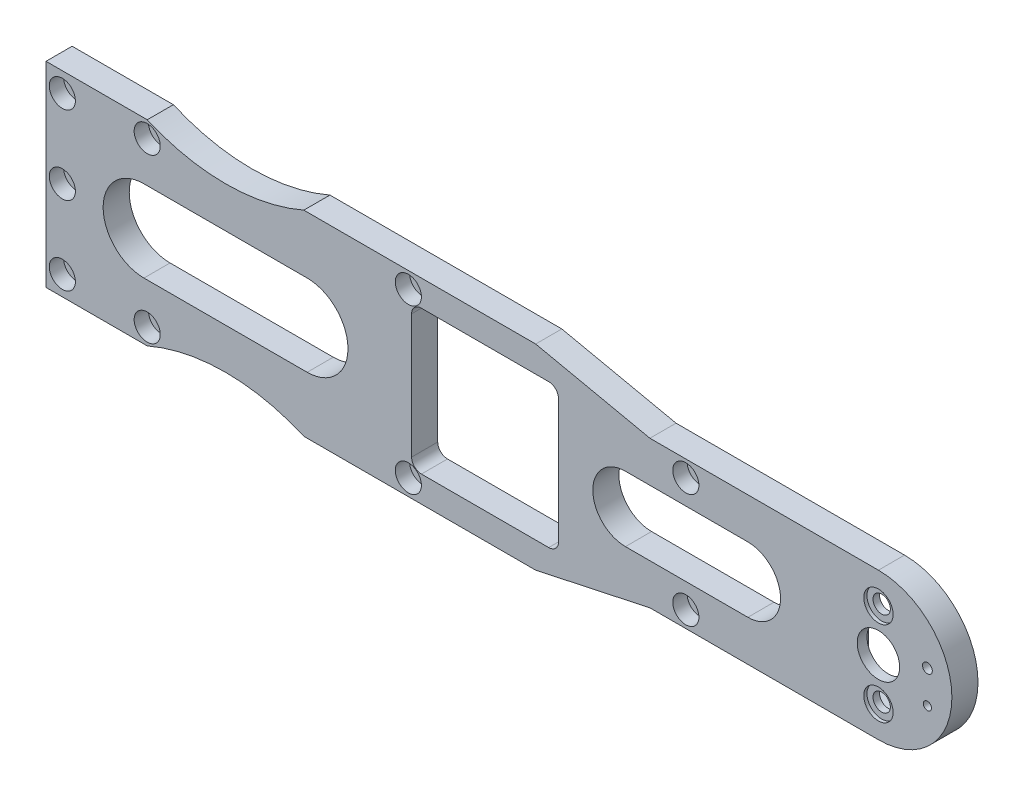
SolidWorks part; units mm, degrees
material "6061 合金"
ref_plane "前视基准面" through (0, 0, 0) normal (0, 0, 1) x (1, 0, 0)
ref_plane "上视基准面" through (0, 0, 0) normal (0, 1, 0) x (1, 0, 0)
ref_plane "右视基准面" through (0, 0, 0) normal (1, 0, 0) x (0, 0, -1)
sketch "草图1" plane through (0, 0, 0) normal (0, 0, 1) x (1, 0, 0)
  line L0 (128.1737, 22.5) -> (58.1737, 22.5)
  line L1 (23.1737, 30) -> (-47.8471, 30)
  line L2 (-96.8263, 0) -> (-46.8263, 0) construction
  line L3 (23.1737, -30) -> (-47.8471, -30)
  line L4 (-126.8263, 30) -> (-126.8263, -30)
  line L5 (-95.8054, 30) -> (-126.8263, 30)
  line L6 (-95.8054, -30) -> (-126.8263, -30)
  line L7 (58.1737, 22.5) -> (23.1737, 30)
  line L8 (-96.8263, 12.5) -> (-46.8263, 12.5)
  line L9 (23.1737, -30) -> (58.1737, -22.5)
  line L10 (58.1737, -22.5) -> (128.1737, -22.5)
  line L11 (-96.8263, -12.5) -> (-46.8263, -12.5)
  line L13 (30.1737, -22) -> (-14.8263, -22)
  line L14 (30.1737, -22) -> (30.1737, 22)
  line L15 (30.1737, 22) -> (-14.8263, 22)
  line L16 (-14.8263, -22) -> (-14.8263, 22)
  line L17 (30.1737, -22) -> (-14.8263, 22) construction
  line L18 (30.1737, 22) -> (-14.8263, -22) construction
  arc A0 (128.1737, -22.5) -> (128.1737, 22.5) centre (128.1737, 0) ccw
  arc A1 (-96.8263, 12.5) -> (-96.8263, -12.5) centre (-96.8263, 0) ccw
  arc A2 (-46.8263, -12.5) -> (-46.8263, 12.5) centre (-46.8263, 0) ccw
  arc A3 (-95.8054, 30) -> (-47.8471, 30) centre (-71.8263, 85) ccw
  arc A4 (-47.8471, -30) -> (-95.8054, -30) centre (-71.8263, -85) ccw
  point P0 (0, 0)
  point P15 (-71.8263, 0)
  point P20 (7.6737, 0)
  dimension "D3" = 45
  dimension "D7" = 12.5
  dimension "D15" = 55
  dimension "D16" = 120
  dimension "D18" = 60
  dimension "D2" = 255
  dimension "D4" = 70
  dimension "D5" = 30
  dimension "D6" = 70
  dimension "D8" = 50
  dimension "D9" = 30
  dimension "D10" = 112
  dimension "D11" = 45
  dimension "D12" = 44
  dimension "D13" = 150
  dimension "D14" = 60
  dimension "D17" = 55
  dimension "D19" = 55
  dimension "D20" = 55
extrude "凸台-拉伸1" add sketch "草图1" along normal blind 8
sketch "草图2" plane through (0, 0, 8) normal (0, 0, 1) x (1, 0, 0)
  line L0 (50.6737, 0) -> (88.1737, 0) construction
  line L1 (50.6737, 10) -> (88.1737, 10)
  line L2 (50.6737, -10) -> (88.1737, -10)
  arc A0 (50.6737, 10) -> (50.6737, -10) centre (50.6737, 0) ccw
  arc A1 (88.1737, -10) -> (88.1737, 10) centre (88.1737, 0) ccw
  point P3 (69.4237, 0)
  dimension "D1" = 40
  dimension "D3" = 10
  dimension "D2" = 37.5
extrude "切除-拉伸1" cut sketch "草图2" against normal blind 10
fillet "圆角1" radius 3 4 edges at (30.1737, -22, 4) (-14.8263, -22, 4) (-14.8263, 22, 4) (30.1737, 22, 4)
hole_wizard "M4 六角凹头螺钉的柱形沉头孔1" positions "草图4" profile "草图3" counterbore size "M4" standard "Iso" end condition through all
sketch "草图4" plane through (0, 0, 8) normal (0, 0, 1) x (1, 0, 0)
  line L0 (-126.8263, 30) -> (-126.8263, -30) construction
  arc A0 (-96.8263, 12.5) -> (-96.8263, -12.5) centre (-96.8263, 0) ccw construction
  point P0 (-121.8263, 0)
  point P2 (-121.8263, -24)
  point P4 (-121.8263, 24)
  point P6 (-95.8263, 25)
  point P8 (-95.8263, -25)
  point P10 (-15.8263, -25)
  point P12 (-15.8263, 25)
  point P18 (-109.3263, 0)
  point P38 (69.1737, 17.5)
  point P40 (69.1737, -17.5)
  dimension "D1" = 5
  dimension "D2" = 24
  dimension "D3" = 24
  dimension "D4" = 0
  dimension "D5" = 26
  dimension "D6" = 80
  dimension "D7" = 50
  dimension "D8" = 25
  dimension "D9" = 85
  dimension "D10" = 35
  dimension "D11" = 17.5
sketch "草图3" plane through (-121.8263, 0, 8) normal (1, 0, 0) x (0, -1, 0)
  line L0 (0, 0) -> (0, 8)
  line L1 (0, 8) -> (2.25, 8)
  line L3 (2.25, 8) -> (2.25, 4.4)
  line L4 (2.25, 4.4) -> (4, 4.4)
  line L5 (4, 4.4) -> (4, 0)
  line L7 (4, 0) -> (0, 0)
  line L11 (0, -6.35) -> (0, 107.95) construction
  dimension "通孔孔直径" = 4.5
  dimension "通孔孔深度" = 8
  dimension "柱形沉头孔直径" = 8
  dimension "柱形沉头孔深度" = 4.4
sketch "草图11" plane through (0, 0, 0) normal (0, 0, -1) x (-1, 0, 0)
  line L0 (24.8263, -27) -> (47.2295, -27)
  line L9 (-88.1737, -13) -> (-50.6737, -13)
  line L10 (-50.6737, 13) -> (-88.1737, 13)
  line L11 (96.423, -27) -> (123.8263, -27)
  line L12 (-88.1737, 20.25) -> (-115.4771, 20.25)
  line L14 (123.8263, 27) -> (96.423, 27)
  line L29 (123.8263, -27) -> (123.8263, 27)
  line L30 (47.2295, 27) -> (-22.8559, 27)
  line L31 (-22.8559, 27) -> (-57.8559, 19.5)
  line L32 (-57.8559, 19.5) -> (-128.1737, 19.5)
  line L38 (-128.1737, -19.5) -> (-57.8559, -19.5)
  line L39 (-57.8559, -19.5) -> (-22.8559, -27)
  line L40 (-22.8559, -27) -> (47.2295, -27)
  line L41 (101.8263, -27) -> (101.8263, -25)
  line L42 (114.8263, 27) -> (101.8263, 27)
  line L45 (-115.2449, -19.5) -> (-88.1737, -19.5)
  line L55 (-100.6534, 3.6412) -> (-112.4771, 3.6412)
  line L60 (96.8263, 15.5) -> (46.8263, 15.5)
  line L61 (46.8263, -15.5) -> (96.8263, -15.5)
  line L62 (96.8263, 15.5) -> (46.8263, 15.5)
  line L63 (46.8263, -15.5) -> (96.8263, -15.5)
  line L65 (-88.1737, 13) -> (-88.1737, 20.25)
  line L66 (-88.1737, -13) -> (-88.1737, -19.5)
  line L70 (101.8263, 27) -> (101.8263, 25)
  line L71 (114.8263, 30) -> (114.8263, -30)
  line L72 (114.8263, 27) -> (114.8263, -27)
  line L74 (47.2295, 27) -> (24.8263, 27)
  line L78 (101.8263, -27) -> (114.8263, -27)
  line L80 (24.8263, 27) -> (24.8263, -27)
  line L83 (-115.4771, 20.25) -> (-115.4771, 9.9216)
  line L86 (-112.2449, -4.3588) -> (-100.4212, -4.3588)
  line L87 (-115.2449, -10.2748) -> (-115.2449, -19.5)
  arc A3 (47.2295, 27) -> (96.423, 27) centre (71.8263, 85) ccw
  arc A4 (47.2295, 27) -> (89.8377, 24.6296) centre (71.8263, 85) ccw
  arc A5 (96.423, -27) -> (47.2295, -27) centre (71.8263, -85) ccw
  arc A6 (89.8377, -24.6296) -> (47.2295, -27) centre (71.8263, -85) ccw
  arc A9 (-128.1737, 19.5) -> (-128.1737, -19.5) centre (-128.1737, 0) ccw
  arc A16 (-50.6737, -13) -> (-50.6737, 13) centre (-50.6737, 0) ccw
  arc A17 (-88.1737, 13) -> (-88.1737, -13) centre (-88.1737, 0) ccw
  arc A18 (101.8263, -25) -> (89.8377, -24.6296) centre (95.8263, -25) ccw
  arc A19 (-88.1737, 13) -> (-100.6534, 3.6412) centre (-88.1737, 0) ccw
  arc A43 (-112.4771, 3.6412) -> (-115.4771, 9.9216) centre (-128.1737, 0) ccw
  arc A47 (-100.4212, -4.3588) -> (-88.1737, -13) centre (-88.1737, 0) ccw
  arc A49 (96.8263, -15.5) -> (96.8263, 15.5) centre (96.8263, 0) ccw
  arc A50 (46.8263, 15.5) -> (46.8263, -15.5) centre (46.8263, 0) ccw
  arc A51 (96.8263, -15.5) -> (96.8263, 15.5) centre (96.8263, 0) ccw
  arc A52 (46.8263, 15.5) -> (46.8263, -15.5) centre (46.8263, 0) ccw
  arc A53 (-115.2449, -10.2748) -> (-112.2449, -4.3588) centre (-128.1737, 0) ccw
  arc A58 (89.8377, 24.6296) -> (101.8263, 25) centre (95.8263, 25) ccw
  dimension "D2" = 3
  dimension "D9" = 6
  dimension "D6" = 3
  dimension "D7" = 8
  dimension "D8" = 3
  dimension "D3" = 90
  dimension "D1" = 3
  dimension "D4" = 3
  dimension "D5" = 12
extrude "切除-拉伸2" cut sketch "草图11" against normal blind 4
fillet "圆角2" radius 1.5 22 edges at (-101.8263, -27, 2) (-114.8263, -27, 2) (-114.8263, 27, 2) (-101.8263, 27, 2) (-24.8263, 27, 2) (88.1737, -19.5, 2) (88.1737, 13, 2) (88.1737, 20.25, 2) (115.4771, 9.9216, 2) (115.4771, 20.25, 2) (100.6534, 3.6412, 2) (112.4771, 3.6412, 2) (115.2449, -19.5, 2) (115.2449, -10.2748, 2) (112.2449, -4.3588, 2) (100.4212, -4.3588, 2) (88.1737, -13, 2) (-89.8377, -24.6296, 2) (-89.8377, 24.6296, 2) (-47.2295, 27, 2) (-47.2295, -27, 2) (-24.8263, -27, 2)
hole_wizard "Ø13.0 (13) 直径孔1" positions "草图13" profile "草图12" hole size "Ø13.0" standard "Gb"
sketch "草图13" plane through (0, 0, 8) normal (0, 0, 1) x (1, 0, 0)
  arc A0 (128.1737, -22.5) -> (128.1737, 22.5) centre (128.1737, 0) ccw construction
  point P0 (128.1737, 0)
  dimension "D1" = 0
sketch "草图12" plane through (128.1737, 0, 8) normal (1, 0, 0) x (0, -1, 0)
  line L0 (0, 0) -> (0, 15.9056)
  line L1 (0, 15.9056) -> (6.5, 12)
  line L2 (6.5, 12) -> (6.5, 0)
  line L5 (6.5, 0) -> (0, 0)
  line L10 (0, 15.9056) -> (-6.5, 12) construction
  line L11 (0, -6.35) -> (0, 107.95) construction
  dimension "孔直径" = 13
  dimension "孔深度" = 12
  dimension "导头角度" = 118
sketch "草图14" plane through (0, 0, 0) normal (0, 0, -1) x (-1, 0, 0)
  line L2 (-139.1737, 14.2478) -> (-139.1737, -14.2478)
  line L4 (-117.1737, 14.2478) -> (-117.1737, -14.2478)
  line L5 (-139.1737, 14.2478) -> (-117.1737, -14.2478) construction
  line L6 (-139.1737, -14.2478) -> (-117.1737, 14.2478) construction
  arc A0 (-117.1737, 14.2478) -> (-139.1737, 14.2478) centre (-128.1737, 0) ccw
  arc A1 (-139.1737, -14.2478) -> (-117.1737, -14.2478) centre (-128.1737, 0) ccw
  point P0 (-128.1737, 0)
  dimension "D2" = 18
  dimension "D1" = 22
extrude "切除-拉伸3" cut sketch "草图14" against normal blind 5
hole_wizard "Ø5.3 (5.3) 直径孔1" positions "草图16" profile "草图15" hole size "Ø5.3" standard "Gb"
sketch "草图16" plane through (0, 0, 8) normal (0, 0, 1) x (1, 0, 0)
  circle A1 centre (128.1737, 0) radius 6.5 construction
  point P0 (128.1737, 13)
  point P2 (128.1737, -13)
  dimension "D2" = 0
  dimension "D1" = 26
  dimension "D3" = 13
sketch "草图15" plane through (128.1737, 13, 8) normal (1, 0, 0) x (0, -1, 0)
  line L0 (0, 0) -> (0, 13.5923)
  line L1 (0, 13.5923) -> (2.65, 12)
  line L2 (2.65, 12) -> (2.65, 0)
  line L5 (2.65, 0) -> (0, 0)
  line L10 (0, 13.5923) -> (-2.65, 12) construction
  line L11 (0, -6.35) -> (0, 107.95) construction
  dimension "孔直径" = 5.3
  dimension "孔深度" = 12
  dimension "导头角度" = 118
sketch "草图19" plane through (0, 0, 8) normal (0, 0, 1) x (1, 0, 0)
  circle A0 centre (128.1737, 13) radius 4.5
  circle A1 centre (128.1737, -13) radius 4.5
  dimension "D1" = 9
extrude "切除-拉伸4" cut sketch "草图19" against normal blind 1
hole_wizard "M3 螺纹孔1" positions "草图21" profile "草图20" tap size "M3" standard "Gb" end condition through all
sketch "草图21" plane through (0, 0, 8) normal (0, 0, 1) x (1, 0, 0)
  point P0 (143.1737, -6)
cosmetic thread "孔螺蚊线1" parameters "D2"=3
sketch "草图20" plane through (143.1737, -6, 8) normal (1, 0, 0) x (0, -1, 0)
  line L0 (0, 0) -> (0, 8)
  line L1 (0, 8) -> (1.25, 8)
  line L2 (1.25, 8) -> (1.25, 0)
  line L5 (1.25, 0) -> (0, 0)
  line L11 (0, -6.35) -> (0, 107.95) construction
  dimension "通孔螺纹孔钻头直径" = 2.5
  dimension "通孔螺纹孔钻头深度" = 8
hole_wizard "Ø3.0 (3) 直径孔1" positions "草图23" profile "草图22" hole size "Ø3.0" standard "Gb"
sketch "草图23" plane through (0, 0, 8) normal (0, 0, 1) x (1, 0, 0)
  point P0 (143.1737, 4)
sketch "草图22" plane through (143.1737, 4, 8) normal (1, 0, 0) x (0, -1, 0)
  line L0 (0, 0) -> (0, 40.9013)
  line L1 (0, 40.9013) -> (1.5, 40)
  line L2 (1.5, 40) -> (1.5, 0)
  line L5 (1.5, 0) -> (0, 0)
  line L10 (0, 40.9013) -> (-1.5, 40) construction
  line L11 (0, -6.35) -> (0, 107.95) construction
  dimension "孔直径" = 3
  dimension "孔深度" = 40
  dimension "导头角度" = 118
fillet "圆角3" radius 1.5 4 edges at (139.1737, -14.2478, 2.5) (117.1737, -14.2478, 2.5) (117.1737, 14.2478, 2.5) (139.1737, 14.2478, 2.5)
